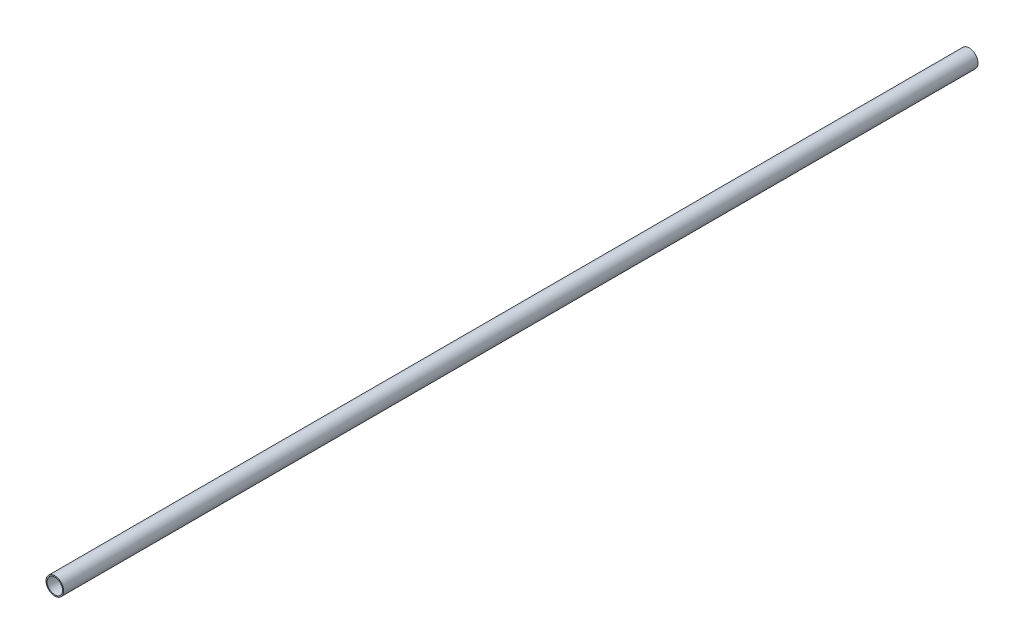
SolidWorks part; units mm, degrees
ref_plane "Plano frontal" through (0, 0, 0) normal (0, 0, 1) x (1, 0, 0)
ref_plane "Plano superior" through (0, 0, 0) normal (0, 1, 0) x (1, 0, 0)
ref_plane "Plano direito" through (0, 0, 0) normal (1, 0, 0) x (0, 0, -1)
sketch "Sketch2" plane through (0, 0, 0) normal (0, 0, 1) x (1, 0, 0)
  circle A0 centre (2449.7201, -5187.0074) radius 24.125
  circle A1 centre (2449.7201, -5187.0074) radius 21.075
  dimension "D1" = 3.05
extrude "Boss-Extrude1" add sketch "Sketch2" along normal blind 2500
